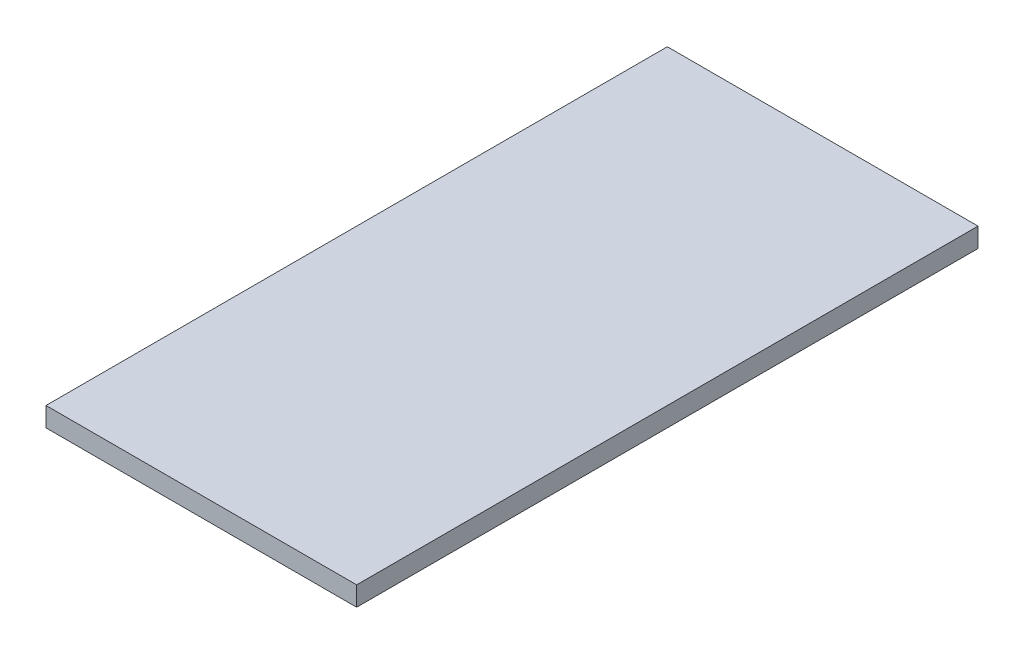
SolidWorks part; units mm, degrees
ref_plane "Front Plane" through (0, 0, 0) normal (0, 0, 1) x (1, 0, 0)
ref_plane "Top Plane" through (0, 0, 0) normal (0, 1, 0) x (1, 0, 0)
ref_plane "Right Plane" through (0, 0, 0) normal (1, 0, 0) x (0, 0, -1)
sketch "Sketch1" plane through (0, 0, 0) normal (0, 1, 0) x (1, 0, 0)
  line L1 (0, 0) -> (203.2, 0)
  line L2 (0, 0) -> (0, 406.4)
  line L3 (0, 406.4) -> (203.2, 406.4)
  line L4 (203.2, 0) -> (203.2, 406.4)
  point P5 (0, 1219.2)
  point P6 (0, 1221.675)
  point P7 (1191.6649, 0)
  point P8 (376.5293, 0)
  point P9 (455.4921, 0)
  point P10 (472.1998, 1011.5945)
  point P11 (281.1236, 457.5699)
  point P12 (421.5932, 0)
  point P13 (495.3053, 0)
  point P14 (498.8341, 395.6947)
  dimension "D1" = 203.2
  dimension "D2" = 406.4
extrude "Boss-Extrude1" add sketch "Sketch1" along normal blind 12.7
